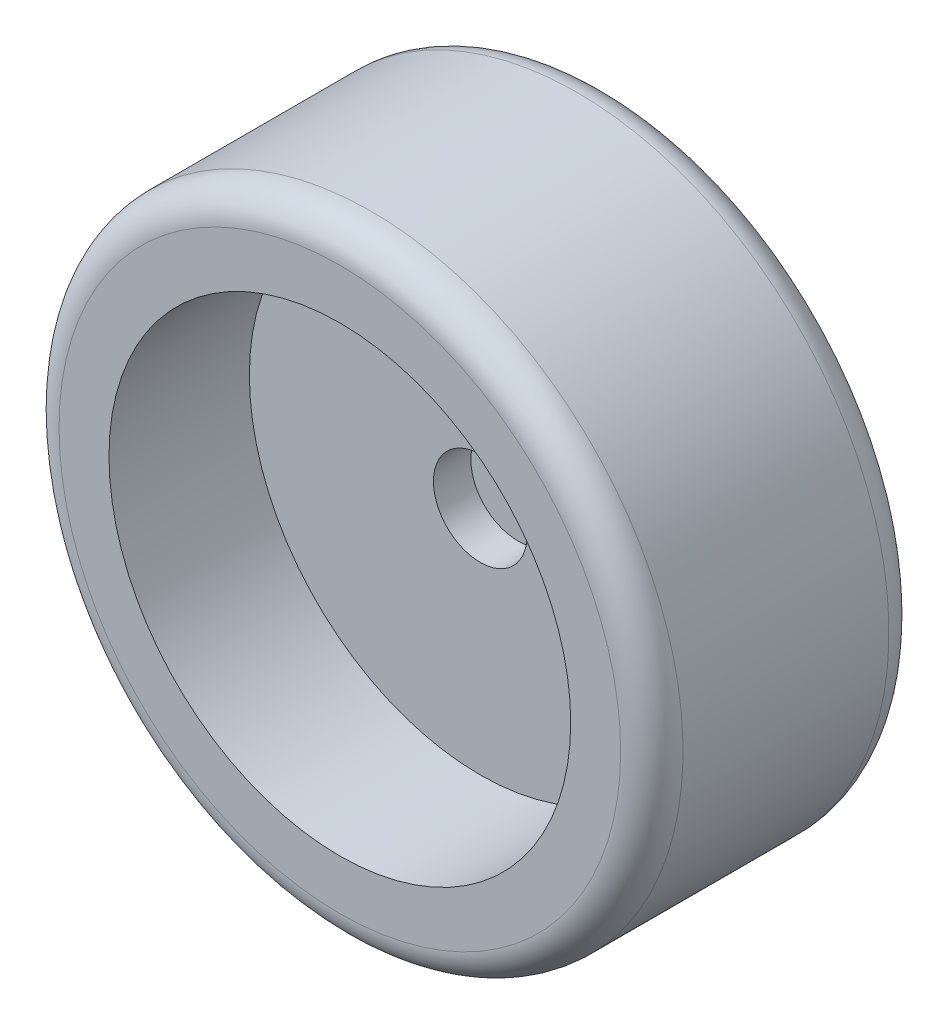
SolidWorks part; units mm, degrees
ref_plane "Front Plane" through (0, 0, 0) normal (0, 0, 1) x (1, 0, 0)
ref_plane "Top Plane" through (0, 0, 0) normal (0, 1, 0) x (1, 0, 0)
ref_plane "Right Plane" through (0, 0, 0) normal (1, 0, 0) x (0, 0, -1)
ref_plane "Plane1" through (0, 0, 0) normal (0, -1, 0) x (1, 0, 0)
sketch "Sketch1" plane through (0, 0, 0) normal (0, -1, 0) x (1, 0, 0)
  line L0 (7.5, 14.5) -> (0, 14.5)
  line L1 (0, 14.5) -> (0, 0)
  line L2 (0, 0) -> (45, 0)
  line L3 (50, 5) -> (50, 38)
  line L4 (45, 43) -> (37, 43)
  line L5 (37, 43) -> (37, 20.5)
  line L6 (37, 20.5) -> (7.5, 20.5)
  line L7 (7.5, 20.5) -> (7.5, 14.5)
  line L8 (0, 43) -> (0, 0) construction
  arc A0 (45, 0) -> (50, 5) centre (45, 5) ccw
  arc A1 (50, 38) -> (45, 43) centre (45, 38) ccw
  dimension "D1" = 50
revolve "Revolve1" add sketch "Sketch1" angle 360 about L8
